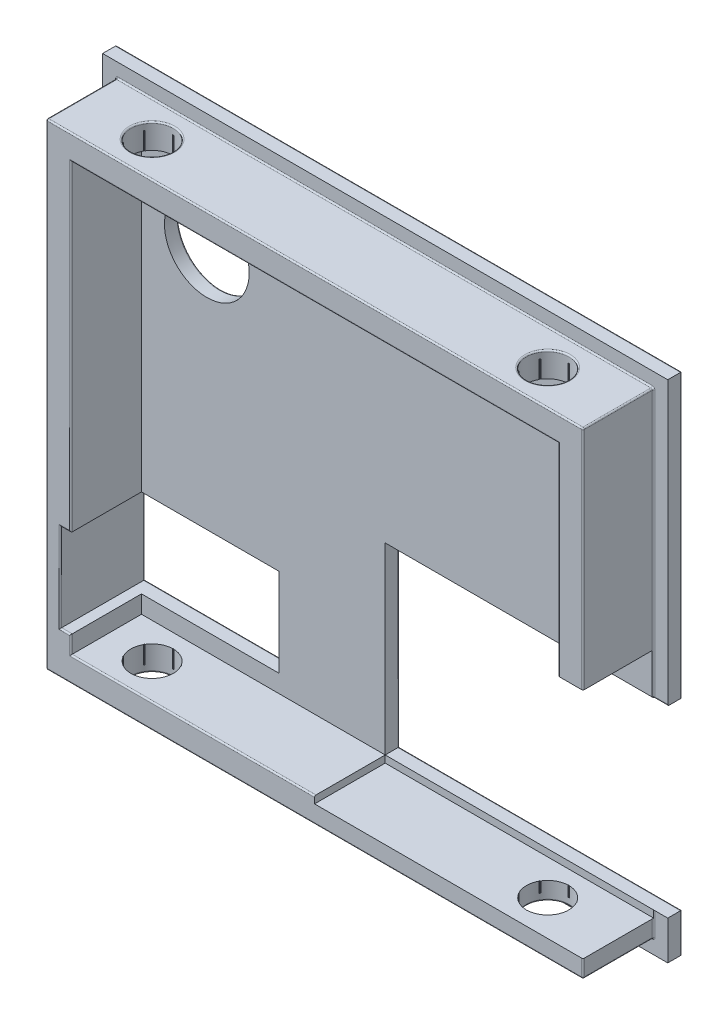
SolidWorks part; units mm, degrees
ref_plane "Plan de face" through (0, 0, 0) normal (0, 0, 1) x (1, 0, 0)
ref_plane "Plan de dessus" through (0, 0, 0) normal (0, 1, 0) x (1, 0, 0)
ref_plane "Plan de droite" through (0, 0, 0) normal (1, 0, 0) x (0, 0, -1)
sketch "Esquisse1" plane through (0, 0, 0) normal (0, 0, 1) x (1, 0, 0)
  line L1 (-40, 35.75) -> (40, 35.75)
  line L2 (-40, 35.75) -> (-40, -35.75)
  line L3 (-40, -35.75) -> (40, -35.75)
  line L4 (40, 35.75) -> (40, -35.75)
  line L5 (-40, 35.75) -> (40, -35.75) construction
  line L6 (-40, -35.75) -> (40, 35.75) construction
  point P0 (0, 0)
  dimension "D1" = 80
  dimension "D2" = 71.5
extrude "Boss.-Extru.1" add sketch "Esquisse1" along normal blind 2
sketch "Esquisse2" plane through (0, 0, 2) normal (0, 0, 1) x (1, 0, 0)
  line L1 (-38, 33.75) -> (38, 33.75)
  line L2 (-38, 33.75) -> (-38, -33.75)
  line L3 (-38, -33.75) -> (38, -33.75)
  line L4 (38, 33.75) -> (38, -33.75)
  line L5 (-38, 33.75) -> (38, -33.75) construction
  line L6 (-38, -33.75) -> (38, 33.75) construction
  line L7 (40, 35.75) -> (-40, 35.75) construction
  line L8 (-34.5, 30.25) -> (34.5, 30.25)
  line L9 (-34.5, 30.25) -> (-34.5, -30.25)
  line L10 (-34.5, -30.25) -> (34.5, -30.25)
  line L11 (34.5, 30.25) -> (34.5, -30.25)
  line L12 (-34.5, 30.25) -> (34.5, -30.25) construction
  line L13 (-34.5, -30.25) -> (34.5, 30.25) construction
  line L15 (40, -35.75) -> (40, 35.75) construction
  line L16 (-40, 35.75) -> (-40, -35.75) construction
  line L17 (-40, -35.75) -> (40, -35.75) construction
  point P0 (-2.3134, -2.0547)
  point P6 (-2.3306, 2.0435)
  dimension "D1" = 3.5
  dimension "D2" = 2
  dimension "D3" = 3.5
  dimension "D4" = 2
  dimension "D5" = 2
  dimension "D6" = 3.5
  dimension "D7" = 2
  dimension "D8" = 3.5
extrude "Boss.-Extru.2" add sketch "Esquisse2" along normal blind 10
sketch "Esquisse4" plane through (0, 30.25, 0) normal (0, -1, 0) x (1, 0, 0)
  line L8 (-28, 10.052) -> (-28, 3.948) construction
  line L9 (-25.3569, 5.474) -> (-25.3569, 8.526)
  line L10 (-25.3569, 8.526) -> (-28, 10.052)
  line L11 (-28, 10.052) -> (-30.6431, 8.526)
  line L12 (-30.6431, 8.526) -> (-30.6431, 5.474)
  line L13 (-30.6431, 5.474) -> (-28, 3.948)
  line L14 (-28, 3.948) -> (-25.3569, 5.474)
  line L15 (-38, 12) -> (38, 12) construction
  circle A0 centre (-28, 7) radius 2.6431 construction
  dimension "D1" = 5
  dimension "D2" = 12
extrude "Enlèv. mat.-Extru.1" cut sketch "Esquisse4" against normal blind 2.5
sketch "Esquisse5" plane through (0, 30.25, 0) normal (0, -1, 0) x (1, 0, 0)
  line L3 (-38, 2) -> (38, 2) construction
  circle A0 centre (-28, 7) radius 3
  dimension "D3" = 6
  dimension "D1" = 5
  dimension "D2" = 12
extrude "Enlèv. mat.-Extru.2" cut sketch "Esquisse5" against normal blind 21
mirror "Symétrie1" about plane through (0, 0, 0) normal (1, 0, 0) of "Enlèv. mat.-Extru.2", "Enlèv. mat.-Extru.1"
mirror "Symétrie2" about plane through (0, 0, 0) normal (0, 1, 0) of "Symétrie1", "Enlèv. mat.-Extru.2", "Enlèv. mat.-Extru.1"
sketch "Esquisse7" plane through (0, 0, 0) normal (0, 0, -1) x (-1, 0, 0)
  line L0 (-40, -30.25) -> (0, -30.25)
  line L1 (-40, -30.25) -> (-40, -4.25)
  line L2 (0, -30.25) -> (0, -4.25)
  line L3 (-40, -4.25) -> (0, -4.25)
  line L4 (-40, -35.75) -> (-40, 35.75) construction
  dimension "D1" = 5.5
  dimension "D2" = 26
  dimension "D3" = 40
extrude "Enlèv. mat.-Extru.3" cut sketch "Esquisse7" against normal blind 15
sketch "Esquisse8" plane through (0, 0, 0) normal (0, 0, -1) x (-1, 0, 0)
  line L0 (-40, -4.25) -> (-40, 35.75) construction
  line L1 (-40, 35.75) -> (40, 35.75) construction
  circle A0 centre (0, 27.75) radius 2.5
  dimension "D1" = 5
  dimension "D2" = 40
  dimension "D3" = 8
extrude "Enlèv. mat.-Extru.4" cut sketch "Esquisse8" against normal blind 5 contours A0
sketch "Esquisse10" plane through (0, 0, 2) normal (0, 0, 1) x (1, 0, 0)
  circle A0 centre (-25.2524, 19.2127) radius 6
  dimension "D1" = 12
extrude "Enlèv. mat.-Extru.5" cut sketch "Esquisse10" against normal blind 5 draft 1 draft outward yes
sketch "Esquisse11" plane through (0, 0, 0) normal (0, 0, -1) x (-1, 0, 0)
  line L0 (15, -15.25) -> (36, -15.25)
  line L1 (15, -15.25) -> (15, -27.75)
  line L2 (36, -15.25) -> (36, -27.75)
  line L3 (15, -27.75) -> (36, -27.75)
  line L4 (40, 35.75) -> (40, -35.75) construction
  line L5 (40, -35.75) -> (-40, -35.75) construction
  dimension "D1" = 21
  dimension "D2" = 12.5
  dimension "D3" = 25
  dimension "D4" = 8
extrude "Enlèv. mat.-Extru.6" cut sketch "Esquisse11" against normal blind 15 contours L3 L2 L0 L1
fillet "Congé1" radius 0.2 43 edges at (39, -4.25, 2) (38, -32, 2) (38, 14.75, 2) (38, -4.25, 7) (38, -33.75, 7) (0, -33.75, 2) (-28, -33.75, 10) (28, -33.75, 10) (-35.25, -27.75, 12) (-34.5, -29, 12) (1.75, -30.25, 12) (38, -32, 12) (0, -33.75, 12) (38, 14.75, 12) (36.25, -4.25, 12) (34.5, 13, 12) (0, 30.25, 12) (-34.5, 7.5, 12) (-35.25, -15.25, 12) (-36, -21.5, 12) (-38, 0, 12) (-38, -33.75, 7) (-38, 0, 2) (38, 33.75, 7) (0, 33.75, 12) (-38, 33.75, 7) (0, 33.75, 2) (-28, 33.75, 4) (28, 33.75, 4) (0, 35.75, 0) (-40, 0, 0) (0, -35.75, 0) (40, -33, 0) (20, -30.25, 0) (0, -17.25, 0) (20, -4.25, 0) (40, 15.75, 0) (-2.5, 27.75, 0) (-19.2175, 19.2127, 0) (-36, -21.5, 0) (-25.5, -15.25, 0) (-15, -21.5, 0) (-25.5, -27.75, 0)
sketch "Esquisse12" plane through (38, 0, 0) normal (1, 0, 0) x (0, 0, -1)
  line L0 (-12, 1.6567) -> (-2, 1.6567)
  line L1 (-12, 1.6567) -> (-12, -4.7724)
  line L2 (-2, 1.6567) -> (-2, -4.7724)
  line L3 (-12, -4.7724) -> (-2, -4.7724)
  line L4 (-12, -4.05) -> (-12, 33.55) construction
  line L8 (-2, -4.05) -> (-2, 35.75) construction
  point P6 (-2, 1.6567)
  point P9 (-2, -4.25)
  point P10 (-2, -4.05)
  point P11 (-2.2, -4.9075)
  point P12 (-2.2, -4.7724)
extrude "Enlèv. mat.-Extru.7" cut sketch "Esquisse12" against normal blind 10
sketch "Esquisse13" plane through (0, -30.25, 0) normal (0, 1, 0) x (1, 0, 0)
  line L0 (0, -2) -> (0, -12)
  line L1 (0, -2) -> (38.0389, -2)
  line L2 (0, -12) -> (38.0389, -12)
  line L3 (38.0389, -2) -> (38.0389, -12)
  line L4 (40, -2) -> (-40, -2) construction
  line L5 (37.8, -12) -> (-37.8, -12) construction
extrude "Enlèv. mat.-Extru.8" cut sketch "Esquisse13" against normal blind 1
